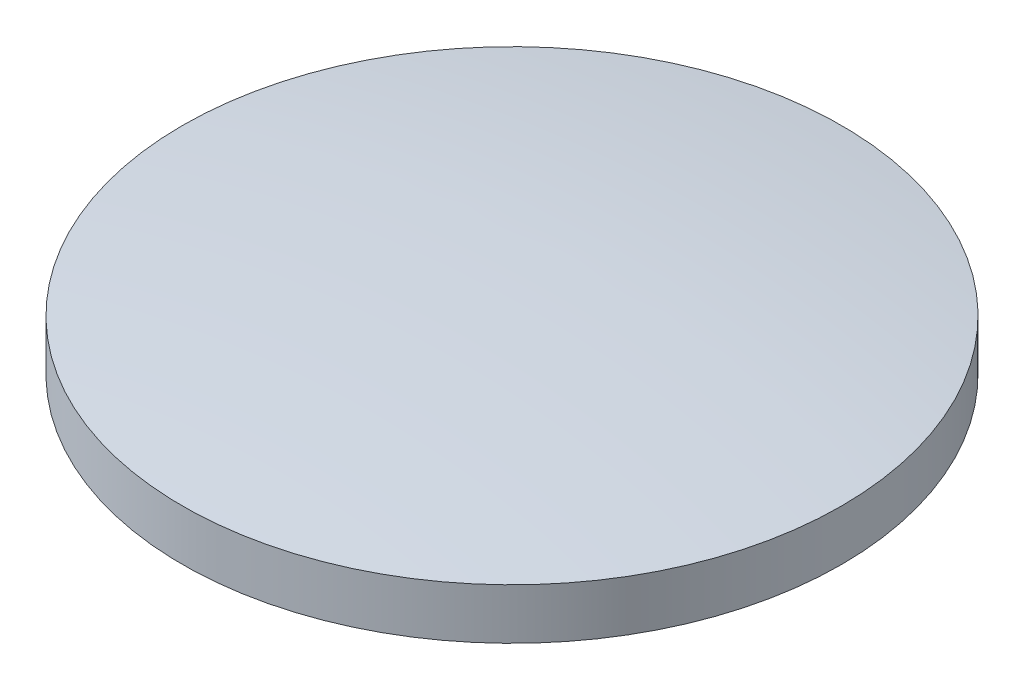
SolidWorks part; units mm, degrees
ref_plane "Front" through (0, 0, 0) normal (0, 0, 1) x (1, 0, 0)
ref_plane "Top" through (0, 0, 0) normal (0, 1, 0) x (1, 0, 0)
ref_plane "Right" through (0, 0, 0) normal (1, 0, 0) x (0, 0, -1)
sketch "Sketch1" plane through (0, 0, 0) normal (0, 0, 1) x (1, 0, 0)
  line L0 (45.5, -5.7526) -> (45.5, -12.7526)
  line L1 (45.5, -12.7526) -> (0, -12.7526)
  line L3 (0, -12.7526) -> (0, -2.62)
  arc A0 (0, -2.62) -> (45.5, -5.7526) centre (0, -334.62) cw
  point P6 (22.8039, -3.4041)
  dimension "D4" = 332
  dimension "D1" = 7
  dimension "D2" = 10.1326
  dimension "D3" = 45.5
revolve "Revolve1" add sketch "Sketch1" angle 360 about L3
